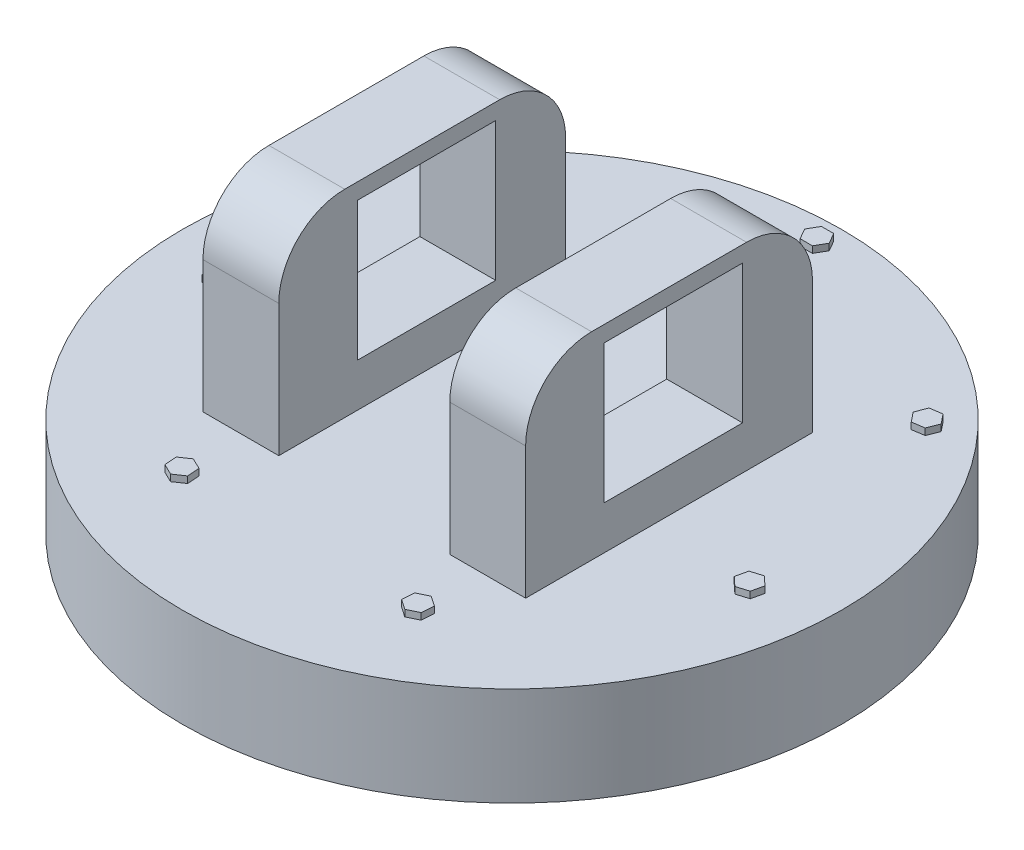
SolidWorks part; units mm, degrees
ref_plane "Ön Düzlem" through (0, 0, 0) normal (0, 0, 1) x (1, 0, 0)
ref_plane "Üst Düzlem" through (0, 0, 0) normal (0, 1, 0) x (1, 0, 0)
ref_plane "Sağ Düzlem" through (0, 0, 0) normal (1, 0, 0) x (0, 0, -1)
sketch "Çizim1" plane through (0, 0, 0) normal (0, 1, 0) x (1, 0, 0)
  circle A0 centre (0, 0) radius 100
  dimension "D1" = 200
extrude "Yükseklik-Ekstrüzyon1" add sketch "Çizim1" along normal blind 10 and the other way blind 20
sketch "Çizim4" plane through (0, 0, 0) normal (0, 1, 0) x (1, 0, 0)
  circle A0 centre (0, 0) radius 2.55
  dimension "D1" = 5.1
extrude "Kes-Ekstrüzyon4" cut sketch "Çizim4" against normal blind 20.2
sketch "Çizim8" plane through (0, 0, 0) normal (0, 1, 0) x (1, 0, 0)
  line L0 (0, 42.2013) -> (0, -44.7987) construction
  line L1 (-48.9346, -44.7987) -> (-25.9346, -44.7987)
  line L2 (-48.9346, -44.7987) -> (-48.9346, 42.2013)
  line L3 (-48.9346, 42.2013) -> (-25.9346, 42.2013)
  line L4 (-25.9346, -44.7987) -> (-25.9346, 42.2013)
  line L5 (-48.9346, -44.7987) -> (-25.9346, 42.2013) construction
  line L6 (-48.9346, 42.2013) -> (-25.9346, -44.7987) construction
  line L7 (48.9346, -44.7987) -> (25.9346, -44.7987)
  line L8 (25.9346, -44.7987) -> (25.9346, 42.2013)
  line L9 (48.9346, 42.2013) -> (25.9346, 42.2013)
  line L10 (48.9346, -44.7987) -> (48.9346, 42.2013)
  line L11 (-48.9346, 42.2013) -> (63.7012, 42.2013) construction
  line L12 (-48.9346, -44.7987) -> (63.7012, -44.7987) construction
  point P0 (-37.4346, -1.2987)
  dimension "D1" = 23
  dimension "D2" = 87
extrude "Yükseklik-Ekstrüzyon5" add sketch "Çizim8" along normal blind 70
sketch "Çizim9" plane through (0, 0, 0) normal (1, 0, 0) x (0, 0, -1)
  line L1 (-21, 23.1508) -> (21, 23.1508)
  line L2 (-21, 23.1508) -> (-21, 65.1508)
  line L3 (-21, 65.1508) -> (21, 65.1508)
  line L4 (21, 23.1508) -> (21, 65.1508)
  line L5 (-21, 23.1508) -> (21, 65.1508) construction
  line L6 (-21, 65.1508) -> (21, 23.1508) construction
  point P0 (0, 44.1508)
  dimension "D1" = 42
  dimension "D2" = 42
extrude "Kes-Ekstrüzyon6" cut sketch "Çizim9" against normal blind 60 and the other way blind 60
sketch "Çizim10" plane through (0, 10, 0) normal (0, 1, 0) x (1, 0, 0)
  line L0 (66.8126, 58.5153) -> (68.174, 61.9839)
  line L1 (3.7262, 92.485) -> (1.8631, 95.712)
  line L2 (1.8631, 95.712) -> (-1.8631, 95.712)
  line L3 (-1.8631, 95.712) -> (-3.7262, 92.485)
  line L4 (-3.7262, 92.485) -> (-1.8631, 89.258)
  line L5 (-1.8631, 89.258) -> (1.8631, 89.258)
  line L6 (1.8631, 89.258) -> (3.7262, 92.485)
  line L7 (68.174, 61.9839) -> (65.8507, 64.8972)
  line L8 (65.8507, 64.8972) -> (62.1661, 64.3418)
  line L9 (62.1661, 64.3418) -> (60.8048, 60.8732)
  line L10 (60.8048, 60.8732) -> (63.128, 57.9599)
  line L11 (63.128, 57.9599) -> (66.8126, 58.5153)
  line L12 (79.5878, -11.9874) -> (83.1484, -10.8891)
  line L13 (83.1484, -10.8891) -> (83.9776, -7.2563)
  line L14 (83.9776, -7.2563) -> (81.2461, -4.7218)
  line L15 (81.2461, -4.7218) -> (77.6854, -5.8202)
  line L16 (77.6854, -5.8202) -> (76.8563, -9.453)
  line L17 (76.8563, -9.453) -> (79.5878, -11.9874)
  line L18 (32.4317, -65.9332) -> (35.5104, -68.0322)
  line L19 (35.5104, -68.0322) -> (38.8676, -66.4155)
  line L20 (38.8676, -66.4155) -> (39.1461, -62.6997)
  line L21 (39.1461, -62.6997) -> (36.0674, -60.6006)
  line L22 (36.0674, -60.6006) -> (32.7102, -62.2174)
  line L23 (32.7102, -62.2174) -> (32.4317, -65.9332)
  line L24 (-39.1461, -62.6997) -> (-38.8676, -66.4155)
  line L25 (-38.8676, -66.4155) -> (-35.5104, -68.0322)
  line L26 (-35.5104, -68.0322) -> (-32.4317, -65.9332)
  line L27 (-32.4317, -65.9332) -> (-32.7102, -62.2174)
  line L28 (-32.7102, -62.2174) -> (-36.0674, -60.6006)
  line L29 (-36.0674, -60.6006) -> (-39.1461, -62.6997)
  line L30 (-81.2461, -4.7218) -> (-83.9776, -7.2563)
  line L31 (-83.9776, -7.2563) -> (-83.1484, -10.8891)
  line L32 (-83.1484, -10.8891) -> (-79.5878, -11.9874)
  line L33 (-79.5878, -11.9874) -> (-76.8563, -9.453)
  line L34 (-76.8563, -9.453) -> (-77.6854, -5.8202)
  line L35 (-77.6854, -5.8202) -> (-81.2461, -4.7218)
  line L36 (-62.1661, 64.3418) -> (-65.8507, 64.8972)
  line L37 (-65.8507, 64.8972) -> (-68.174, 61.9839)
  line L38 (-68.174, 61.9839) -> (-66.8126, 58.5153)
  line L39 (-66.8126, 58.5153) -> (-63.128, 57.9599)
  line L40 (-63.128, 57.9599) -> (-60.8048, 60.8732)
  line L41 (-60.8048, 60.8732) -> (-62.1661, 64.3418)
  circle A0 centre (0, 92.485) radius 3.227 construction
  point P46 (0, 10)
  dimension "D1" = 7
extrude "Yükseklik-Ekstrüzyon6" add sketch "Çizim10" along normal blind 2
fillet "Radyus1" radius 20 4 edges at (37.4346, 70, -42.2013) (37.4346, 70, 44.7987) (-37.4346, 70, -42.2013) (-37.4346, 70, 44.7987)
